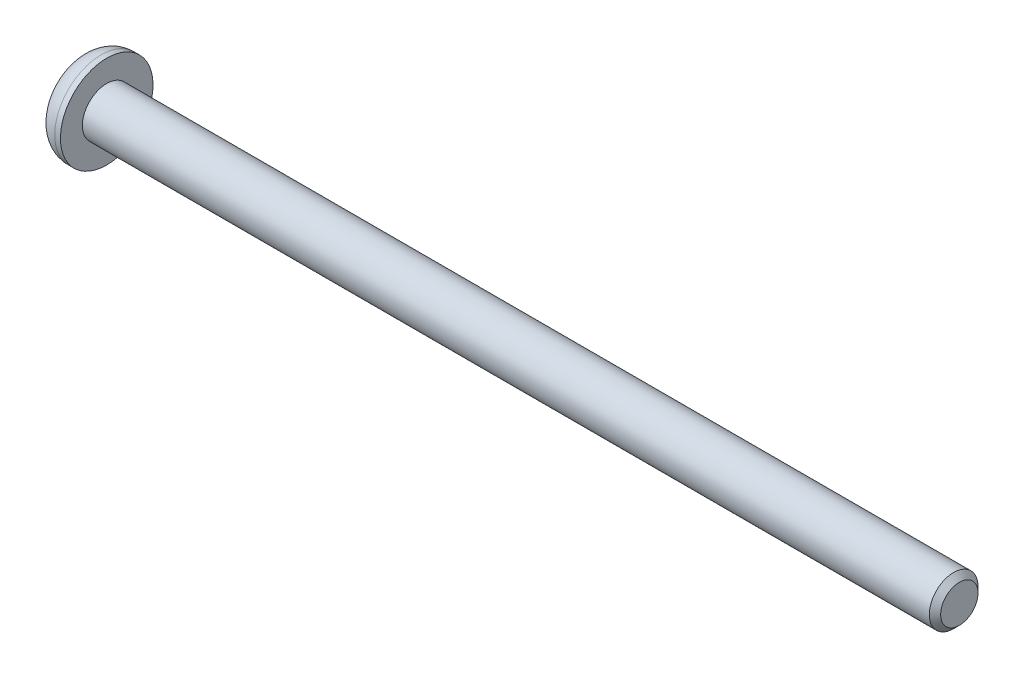
SolidWorks part; units mm, degrees
ref_plane "Ön Düzlem" through (0, 0, 0) normal (0, 0, 1) x (1, 0, 0)
ref_plane "Üst Düzlem" through (0, 0, 0) normal (0, 1, 0) x (1, 0, 0)
ref_plane "Sağ Düzlem" through (0, 0, 0) normal (1, 0, 0) x (0, 0, -1)
sketch "Çizim1" plane through (0, 0, 0) normal (0, 0, 1) x (1, 0, 0)
  line L0 (0, 0) -> (108.3, 0)
  line L1 (0, 0) -> (0, 2.85)
  line L2 (2.6, 5.7) -> (3.3, 5.7)
  line L3 (3.3, 5.7) -> (3.3, 3)
  line L4 (3.3, 3) -> (108.3, 3)
  line L5 (108.3, 3) -> (108.3, 0)
  arc A0 (2.6, 5.7) -> (0, 2.85) centre (2.6, 3.089) ccw
  point P6 (2.95, 5.7)
  dimension "D1" = 105
  dimension "D2" = 3
  dimension "D3" = 5.7
  dimension "D4" = 0.7
  dimension "D5" = 2.85
  dimension "D6" = 3.3
revolve "Döndür1" add sketch "Çizim1" angle 360 about L0
chamfer "Pah1" distance 0.7 angle 45 1 edges at (108.3, -3, 0)
sketch "Çizim2" plane through (0, 0, 0) normal (-1, 0, 0) x (0, 0, 1)
  line L1 (0, 1.6454) -> (-1.425, 0.8227)
  line L2 (-1.425, 0.8227) -> (-1.425, -0.8227)
  line L3 (-1.425, -0.8227) -> (0, -1.6454)
  line L4 (0, -1.6454) -> (1.425, -0.8227)
  line L5 (1.425, -0.8227) -> (1.425, 0.8227)
  line L6 (1.425, 0.8227) -> (0, 1.6454)
  circle A0 centre (0, 0) radius 1.425 construction
  dimension "D1" = 2.85
extrude "Kes-Ekstrüzyon1" cut sketch "Çizim2" against normal blind 1.5
